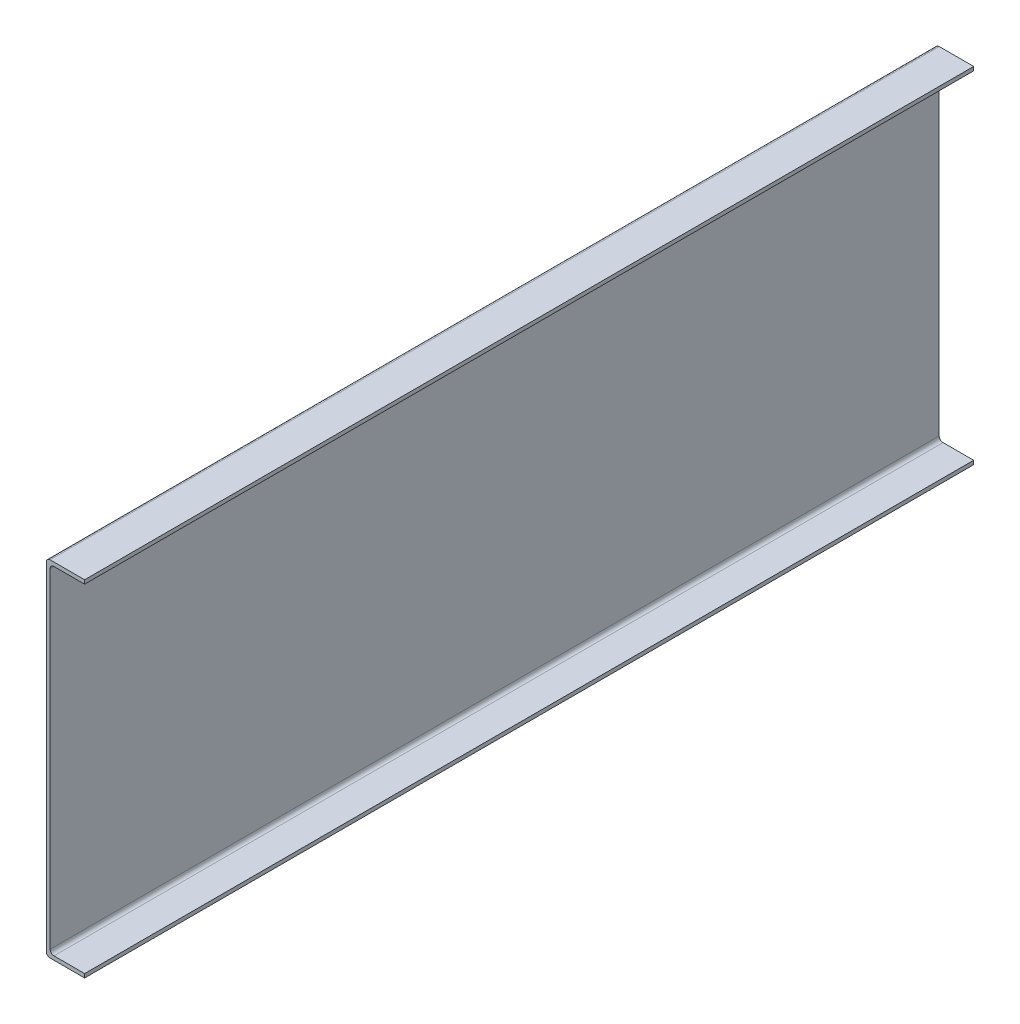
SolidWorks part; units mm, degrees
ref_plane "Front Plane" through (0, 0, 0) normal (0, 0, 1) x (1, 0, 0)
ref_plane "Top Plane" through (0, 0, 0) normal (0, 1, 0) x (1, 0, 0)
ref_plane "Right Plane" through (0, 0, 0) normal (1, 0, 0) x (0, 0, -1)
sketch "Sketch1" plane through (0, 0, 0) normal (0, 0, 1) x (1, 0, 0)
  line L0 (0, -45) -> (0, 45)
  line L1 (0, 45) -> (10, 45)
  line L2 (10, 45) -> (10, 44)
  line L3 (10, 44) -> (1, 44)
  line L4 (1, 44) -> (1, -44)
  line L5 (1, -44) -> (10, -44)
  line L6 (10, -44) -> (10, -45)
  line L7 (10, -45) -> (0, -45)
  point P4 (0, 0)
  dimension "D1" = 1
  dimension "D2" = 1
  dimension "D3" = 1
  dimension "D4" = 10
  dimension "D5" = 90
  dimension "D6" = 10
extrude "Boss-Extrude1" add sketch "Sketch1" along normal blind 232
fillet "Fillet1" radius 1 4 edges at (1, 44, 116) (1, -44, 116) (0, -45, 116) (0, 45, 116)
